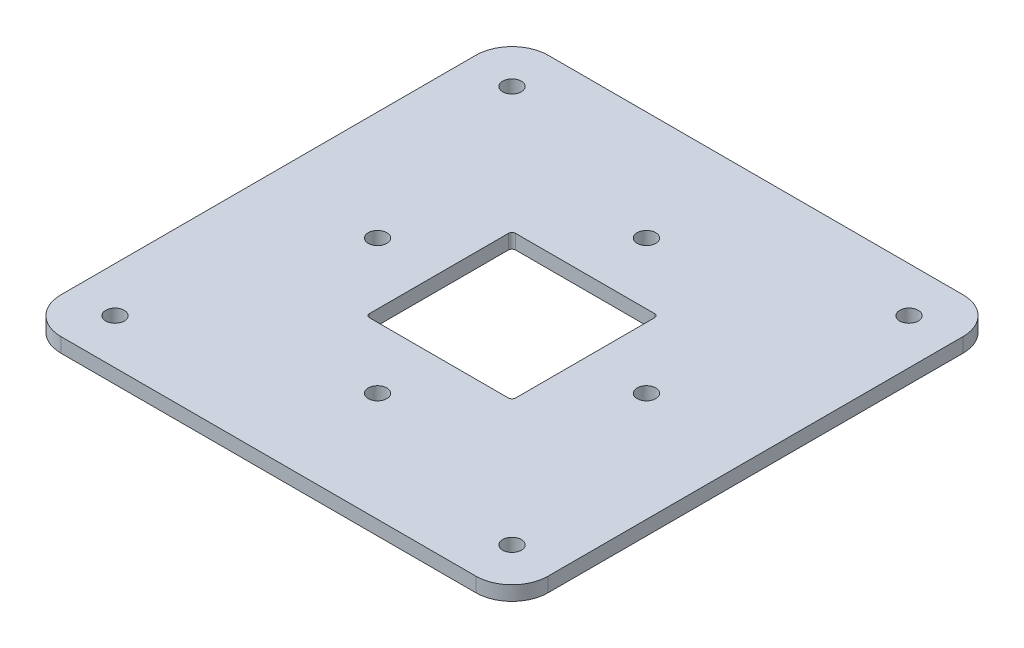
SolidWorks part; units mm, degrees
material "Stainless Steel (ferritic)"
ref_plane "Front Plane" through (0, 0, 0) normal (0, 0, 1) x (1, 0, 0)
ref_plane "Top Plane" through (0, 0, 0) normal (0, 1, 0) x (1, 0, 0)
ref_plane "Right Plane" through (0, 0, 0) normal (1, 0, 0) x (0, 0, -1)
sketch "Sketch1" plane through (0, 0, 0) normal (0, 1, 0) x (1, 0, 0)
  line L1 (-67.5, 67.5) -> (67.5, 67.5)
  line L2 (-67.5, 67.5) -> (-67.5, -67.5)
  line L3 (-67.5, -67.5) -> (67.5, -67.5)
  line L4 (67.5, 67.5) -> (67.5, -67.5)
  line L5 (-67.5, 67.5) -> (67.5, -67.5) construction
  line L6 (-67.5, -67.5) -> (67.5, 67.5) construction
  point P0 (0, 0)
  dimension "D1" = 135
extrude "Boss-Extrude1" add sketch "Sketch1" along normal blind 4
sketch "Sketch4" plane through (0, 4, 0) normal (0, 1, 0) x (1, 0, 0)
  line L1 (-19.25, 20.25) -> (19.25, 20.25)
  line L2 (-20.25, 19.25) -> (-20.25, -19.25)
  line L3 (-19.25, -20.25) -> (19.25, -20.25)
  line L4 (20.25, 19.25) -> (20.25, -19.25)
  line L5 (-20.25, 20.25) -> (20.25, -20.25) construction
  line L6 (-20.25, -20.25) -> (20.25, 20.25) construction
  arc A0 (-20.25, -19.25) -> (-19.25, -20.25) centre (-19.25, -19.25) ccw
  arc A1 (19.25, -20.25) -> (20.25, -19.25) centre (19.25, -19.25) ccw
  arc A2 (19.25, 20.25) -> (20.25, 19.25) centre (19.25, 19.25) cw
  arc A3 (-19.25, 20.25) -> (-20.25, 19.25) centre (-19.25, 19.25) ccw
  point P0 (0, 0)
  dimension "D3" = 1
  dimension "D1" = 40.5
  dimension "D2" = 40.5
extrude "Cut-Extrude1" cut sketch "Sketch4" against normal through all
sketch "Sketch5" plane through (0, 4, 0) normal (0, 1, 0) x (1, 0, 0)
  line L0 (0, 0) -> (-37.25, 0) construction
  line L1 (-20.25, 19.25) -> (-20.25, -19.25) construction
  line L2 (0, 0) -> (-37.25, 0) construction
  line L3 (0, 0) -> (0, 37.25) construction
  circle A0 centre (-37.25, 0) radius 2.58
  circle A1 centre (0, 37.25) radius 2.58
  circle A2 centre (37.25, 0) radius 2.58
  circle A3 centre (0, -37.25) radius 2.58
  point P4 (-20.25, 0)
  dimension "D1" = 5.16
  dimension "D2" = 17
  dimension "D4" = 90
  dimension "D5" = 37.25
  dimension "D3" = 4
extrude "Cut-Extrude2" cut sketch "Sketch5" against normal through all
sketch "Sketch6" plane through (0, 4, 0) normal (0, 1, 0) x (1, 0, 0)
  line L0 (-55, 55) -> (-67.5, 55) construction
  line L1 (-67.5, 67.5) -> (-67.5, -67.5) construction
  line L2 (-55, 55) -> (-55, 67.5) construction
  line L3 (67.5, 67.5) -> (-67.5, 67.5) construction
  line L4 (-55, 55) -> (55, 55) construction
  line L5 (-55, 55) -> (-55, -55) construction
  line L6 (55, -55) -> (55, -67.5) construction
  line L7 (-67.5, -67.5) -> (67.5, -67.5) construction
  circle A0 centre (-55, 55) radius 2.58
  circle A1 centre (55, 55) radius 2.58
  circle A2 centre (55, -55) radius 2.58
  circle A3 centre (-55, -55) radius 2.58
  dimension "D1" = 5.16
  dimension "D4" = 90
  dimension "D5" = 110
  dimension "D6" = 110
  dimension "D2" = 2
  dimension "D3" = 2
extrude "Cut-Extrude3" cut sketch "Sketch6" against normal through all
fillet "Fillet1" radius 10 4 edges at (67.5, 2, -67.5) (67.5, 2, 67.5) (-67.5, 2, 67.5) (-67.5, 2, -67.5)
